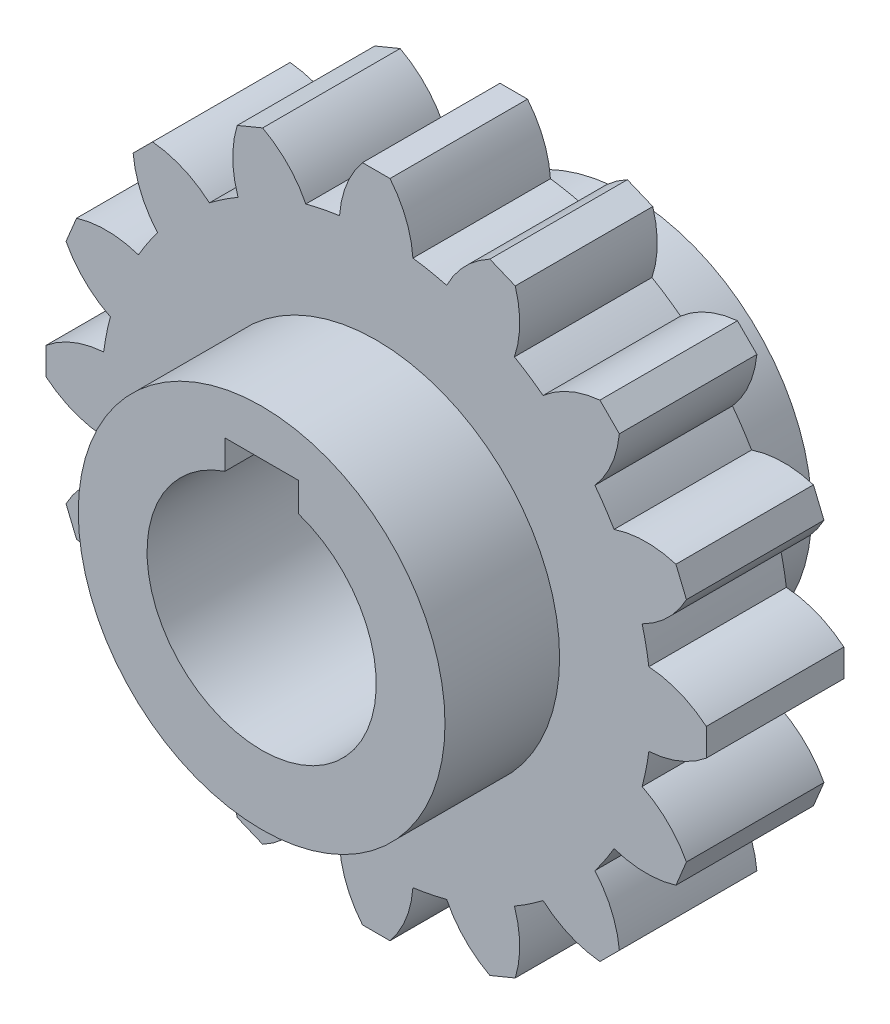
SolidWorks part; units mm, degrees
ref_plane "Front Plane" through (0, 0, 0) normal (0, 0, 1) x (1, 0, 0)
ref_plane "Top Plane" through (0, 0, 0) normal (0, 1, 0) x (1, 0, 0)
ref_plane "Right Plane" through (0, 0, 0) normal (1, 0, 0) x (0, 0, -1)
sketch "Sketch1" plane through (0, 0, 0) normal (0, 0, 1) x (1, 0, 0)
  line L0 (0, 0) -> (0, 36) construction
  line L1 (-1.5, 36) -> (1.5, 36)
  line L2 (12.3908, 33.8337) -> (15.1624, 32.6856)
  line L3 (24.3952, 26.5165) -> (26.5165, 24.3952)
  line L4 (32.6856, 15.1624) -> (33.8337, 12.3908)
  line L5 (36, 1.5) -> (36, -1.5)
  line L6 (33.8337, -12.3908) -> (32.6856, -15.1624)
  line L7 (26.5165, -24.3952) -> (24.3952, -26.5165)
  line L8 (15.1624, -32.6856) -> (12.3908, -33.8337)
  line L9 (1.5, -36) -> (-1.5, -36)
  line L10 (-12.3908, -33.8337) -> (-15.1624, -32.6856)
  line L11 (-24.3952, -26.5165) -> (-26.5165, -24.3952)
  line L12 (-32.6856, -15.1624) -> (-33.8337, -12.3908)
  line L13 (-36, -1.5) -> (-36, 1.5)
  line L14 (-33.8337, 12.3908) -> (-32.6856, 15.1624)
  line L15 (-26.5165, 24.3952) -> (-24.3952, 26.5165)
  line L16 (-15.1624, 32.6856) -> (-12.3908, 33.8337)
  arc A0 (-4, 29.7321) -> (-7.6825, 28.9996) centre (0, 0) ccw
  arc A1 (1.5, 36) -> (4, 29.7321) centre (-6.9748, 28.9873) cw
  arc A2 (-1.5, 36) -> (-4, 29.7321) centre (6.9748, 28.9873) ccw
  arc A3 (12.3908, 33.8337) -> (7.6825, 28.9996) centre (17.5368, 24.1116) ccw
  arc A4 (15.1624, 32.6856) -> (15.0735, 25.9382) centre (4.6491, 29.4499) cw
  arc A5 (24.3952, 26.5165) -> (18.1954, 23.8522) centre (25.429, 15.5652) ccw
  arc A6 (26.5165, 24.3952) -> (23.8522, 18.1954) centre (15.5652, 25.429) cw
  arc A7 (32.6856, 15.1624) -> (25.9382, 15.0735) centre (29.4499, 4.6491) ccw
  arc A8 (33.8337, 12.3908) -> (28.9996, 7.6825) centre (24.1116, 17.5368) cw
  arc A9 (36, 1.5) -> (29.7321, 4) centre (28.9873, -6.9748) ccw
  arc A10 (36, -1.5) -> (29.7321, -4) centre (28.9873, 6.9748) cw
  arc A11 (33.8337, -12.3908) -> (28.9996, -7.6825) centre (24.1116, -17.5368) ccw
  arc A12 (32.6856, -15.1624) -> (25.9382, -15.0735) centre (29.4499, -4.6491) cw
  arc A13 (26.5165, -24.3952) -> (23.8522, -18.1954) centre (15.5652, -25.429) ccw
  arc A14 (24.3952, -26.5165) -> (18.1954, -23.8522) centre (25.429, -15.5652) cw
  arc A15 (15.1624, -32.6856) -> (15.0735, -25.9382) centre (4.6491, -29.4499) ccw
  arc A16 (12.3908, -33.8337) -> (7.6825, -28.9996) centre (17.5368, -24.1116) cw
  arc A17 (1.5, -36) -> (4, -29.7321) centre (-6.9748, -28.9873) ccw
  arc A18 (-1.5, -36) -> (-4, -29.7321) centre (6.9748, -28.9873) cw
  arc A19 (-12.3908, -33.8337) -> (-7.6825, -28.9996) centre (-17.5368, -24.1116) ccw
  arc A20 (-15.1624, -32.6856) -> (-15.0735, -25.9382) centre (-4.6491, -29.4499) cw
  arc A21 (-24.3952, -26.5165) -> (-18.1954, -23.8522) centre (-25.429, -15.5652) ccw
  arc A22 (-26.5165, -24.3952) -> (-23.8522, -18.1954) centre (-15.5652, -25.429) cw
  arc A23 (-32.6856, -15.1624) -> (-25.9382, -15.0735) centre (-29.4499, -4.6491) ccw
  arc A24 (-33.8337, -12.3908) -> (-28.9996, -7.6825) centre (-24.1116, -17.5368) cw
  arc A25 (-36, -1.5) -> (-29.7321, -4) centre (-28.9873, 6.9748) ccw
  arc A26 (-36, 1.5) -> (-29.7321, 4) centre (-28.9873, -6.9748) cw
  arc A27 (-33.8337, 12.3908) -> (-28.9996, 7.6825) centre (-24.1116, 17.5368) ccw
  arc A28 (-32.6856, 15.1624) -> (-25.9382, 15.0735) centre (-29.4499, 4.6491) cw
  arc A29 (-26.5165, 24.3952) -> (-23.8522, 18.1954) centre (-15.5652, 25.429) ccw
  arc A30 (-24.3952, 26.5165) -> (-18.1954, 23.8522) centre (-25.429, 15.5652) cw
  arc A31 (-15.1624, 32.6856) -> (-15.0735, 25.9382) centre (-4.6491, 29.4499) ccw
  arc A32 (-12.3908, 33.8337) -> (-7.6825, 28.9996) centre (-17.5368, 24.1116) cw
  arc A33 (7.6825, 28.9996) -> (4, 29.7321) centre (0, 0) ccw
  arc A34 (18.1954, 23.8522) -> (15.0735, 25.9382) centre (0, 0) ccw
  arc A35 (29.7321, 4) -> (28.9996, 7.6825) centre (0, 0) ccw
  arc A36 (25.9382, 15.0735) -> (23.8522, 18.1954) centre (0, 0) ccw
  arc A37 (28.9996, -7.6825) -> (29.7321, -4) centre (0, 0) ccw
  arc A38 (23.8522, -18.1954) -> (25.9382, -15.0735) centre (0, 0) ccw
  arc A39 (-7.6825, -28.9996) -> (-4, -29.7321) centre (0, 0) ccw
  arc A40 (-18.1954, -23.8522) -> (-15.0735, -25.9382) centre (0, 0) ccw
  arc A41 (-25.9382, -15.0735) -> (-23.8522, -18.1954) centre (0, 0) ccw
  arc A42 (-29.7321, -4) -> (-28.9996, -7.6825) centre (0, 0) ccw
  arc A43 (-28.9996, 7.6825) -> (-29.7321, 4) centre (0, 0) ccw
  arc A44 (-23.8522, 18.1954) -> (-25.9382, 15.0735) centre (0, 0) ccw
  arc A45 (-15.0735, 25.9382) -> (-18.1954, 23.8522) centre (0, 0) ccw
  arc A46 (4, -29.7321) -> (7.6825, -28.9996) centre (0, 0) ccw
  arc A47 (15.0735, -25.9382) -> (18.1954, -23.8522) centre (0, 0) ccw
  point P7 (0, 36)
  dimension "D1" = 60
  dimension "D3" = 11
  dimension "D2" = 6
  dimension "D4" = 8
  dimension "D5" = 3
  dimension "D6" = 16
extrude "Boss-Extrude1" add sketch "Sketch1" along normal mid plane 15
sketch "Sketch2" plane through (0, 0, 0) normal (0, 0, 1) x (1, 0, 0)
  circle A0 centre (0, 0) radius 20
  dimension "D1" = 40
extrude "Boss-Extrude2" add sketch "Sketch2" along normal mid plane 40
sketch "Sketch3" plane through (0, 0, 20) normal (0, 0, 1) x (1, 0, 0)
  line L0 (0, 0) -> (0, 15) construction
  line L1 (-4, 11.8427) -> (-4, 15)
  line L2 (-4, 15) -> (4, 15)
  line L3 (4, 15) -> (4, 11.8427)
  arc A0 (-4, 11.8427) -> (4, 11.8427) centre (0, 0) ccw
  point P6 (0, 0)
  point P9 (0, 14.7083)
  dimension "D2" = 25
  dimension "D1" = 15
  dimension "D3" = 8
extrude "Cut-Extrude1" cut sketch "Sketch3" against normal through all
